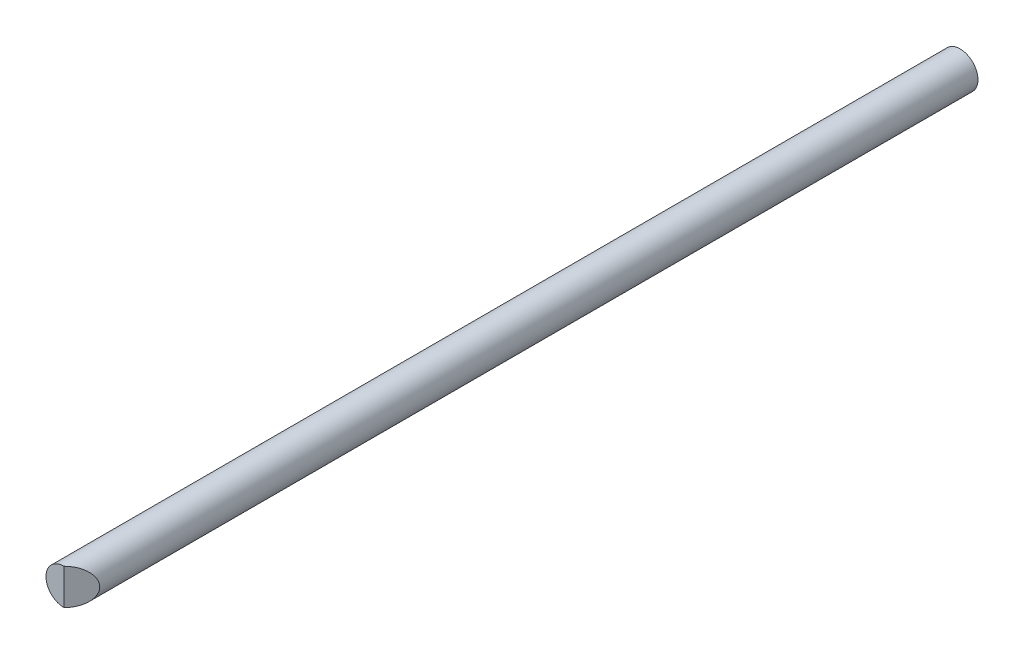
SolidWorks part; units mm, degrees
ref_plane "前视基准面" through (0, 0, 0) normal (0, 0, 1) x (1, 0, 0)
ref_plane "上视基准面" through (0, 0, 0) normal (0, 1, 0) x (1, 0, 0)
ref_plane "右视基准面" through (0, 0, 0) normal (1, 0, 0) x (0, 0, -1)
sketch "草图1" plane through (0, 0, 0) normal (0, 0, 1) x (1, 0, 0)
  circle A0 centre (0, 0) radius 0.5
  dimension "D1" = 1
extrude "凸台-拉伸1" add sketch "草图1" along normal blind 25
sketch "草图2" plane through (0, 0, 0) normal (0, 1, 0) x (1, 0, 0)
  line L0 (0, -25) -> (0.5, -24.5)
  line L2 (-0.5, -25) -> (0.5, -25) construction
  line L3 (0.5, -24.5) -> (0.5, -25)
  line L4 (0.5, -25) -> (0, -25)
  dimension "D1" = 45
extrude "切除-拉伸1" cut sketch "草图2" against normal mid plane 25
